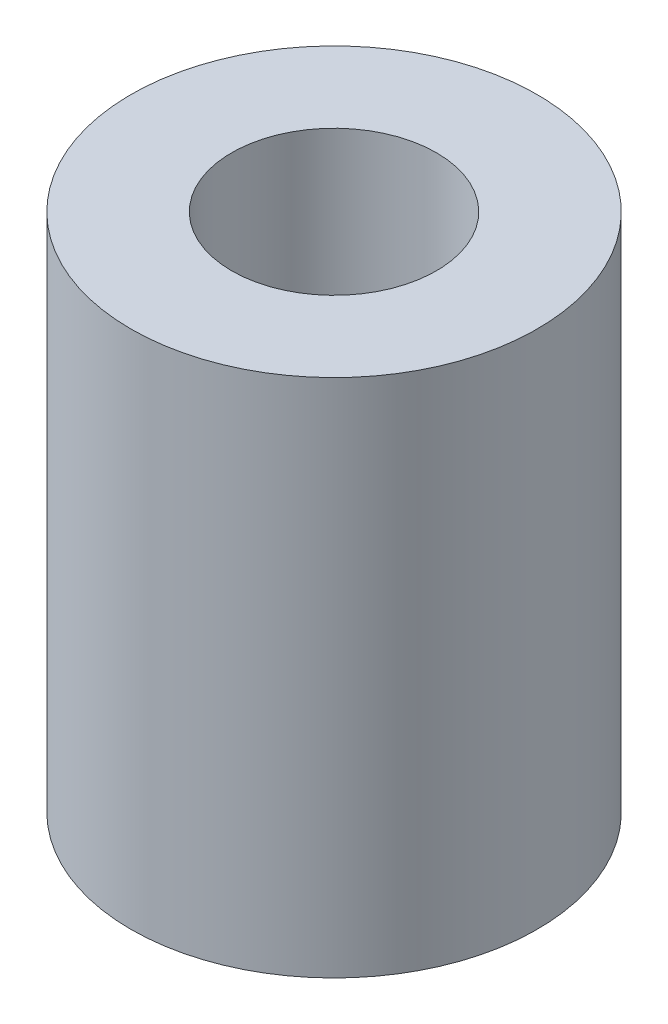
SolidWorks part; units mm, degrees
ref_plane "Front Plane" through (0, 0, 0) normal (0, 0, 1) x (1, 0, 0)
ref_plane "Top Plane" through (0, 0, 0) normal (0, 1, 0) x (1, 0, 0)
ref_plane "Right Plane" through (0, 0, 0) normal (1, 0, 0) x (0, 0, -1)
sketch "Sketch1" plane through (0, 0, 0) normal (0, 1, 0) x (1, 0, 0)
  circle A0 centre (0, 0) radius 7.9375
  dimension "D1" = 15.875
extrude "Boss-Extrude1" add sketch "Sketch1" along normal blind 20.32
sketch "Sketch2" plane through (0, 20.32, 0) normal (0, 1, 0) x (1, 0, 0)
  circle A0 centre (0, 0) radius 4
  dimension "D1" = 8
sketch "Sketch3" plane through (0, 20.32, 0) normal (0, 1, 0) x (1, 0, 0)
  circle A0 centre (0, 0) radius 4
  dimension "D1" = 8
extrude "Cut-Extrude2" cut sketch "Sketch3" against normal through all
